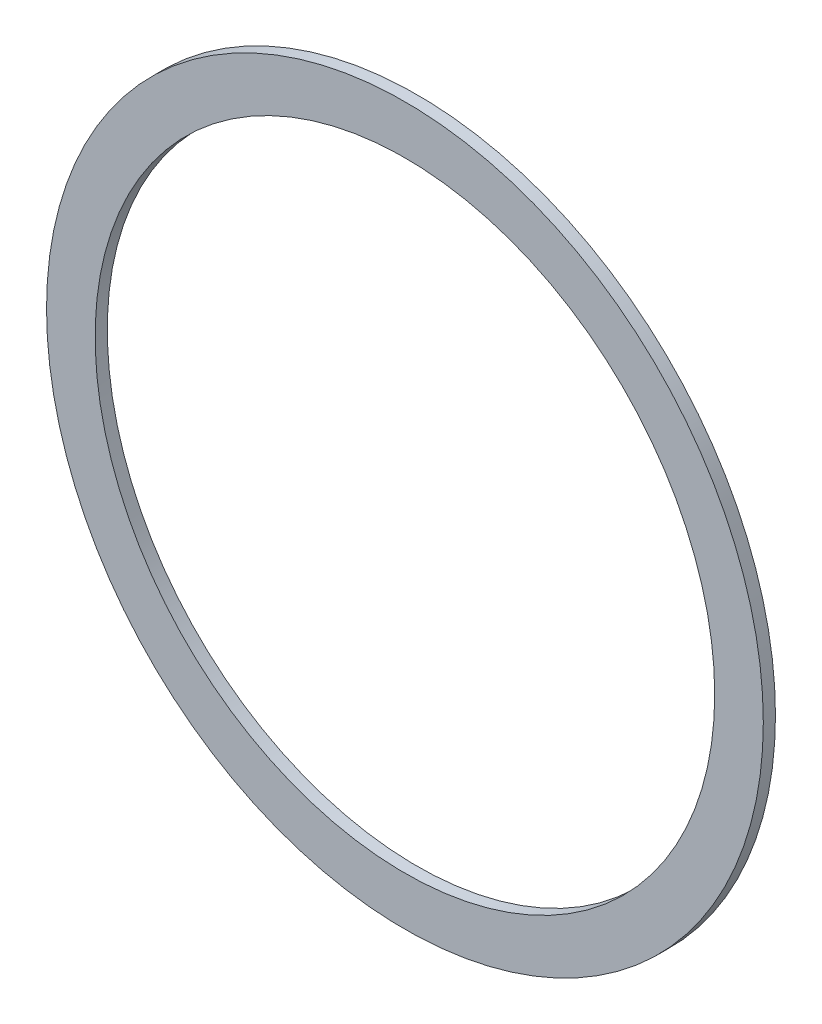
SolidWorks part; units mm, degrees
material "AISI 316 Stainless Steel Sheet (SS)"
ref_plane "Front Plane" through (0, 0, 0) normal (0, 0, 1) x (1, 0, 0)
ref_plane "Top Plane" through (0, 0, 0) normal (0, 1, 0) x (1, 0, 0)
ref_plane "Right Plane" through (0, 0, 0) normal (1, 0, 0) x (0, 0, -1)
sketch "Sketch1" plane through (0, 0, 0) normal (0, 0, 1) x (1, 0, 0)
  circle A0 centre (0, 0) radius 295
  circle A1 centre (0, 0) radius 255
  dimension "D1" = 510
  dimension "D2" = 590
extrude "Boss-Extrude1" add sketch "Sketch1" along normal mid plane 10
